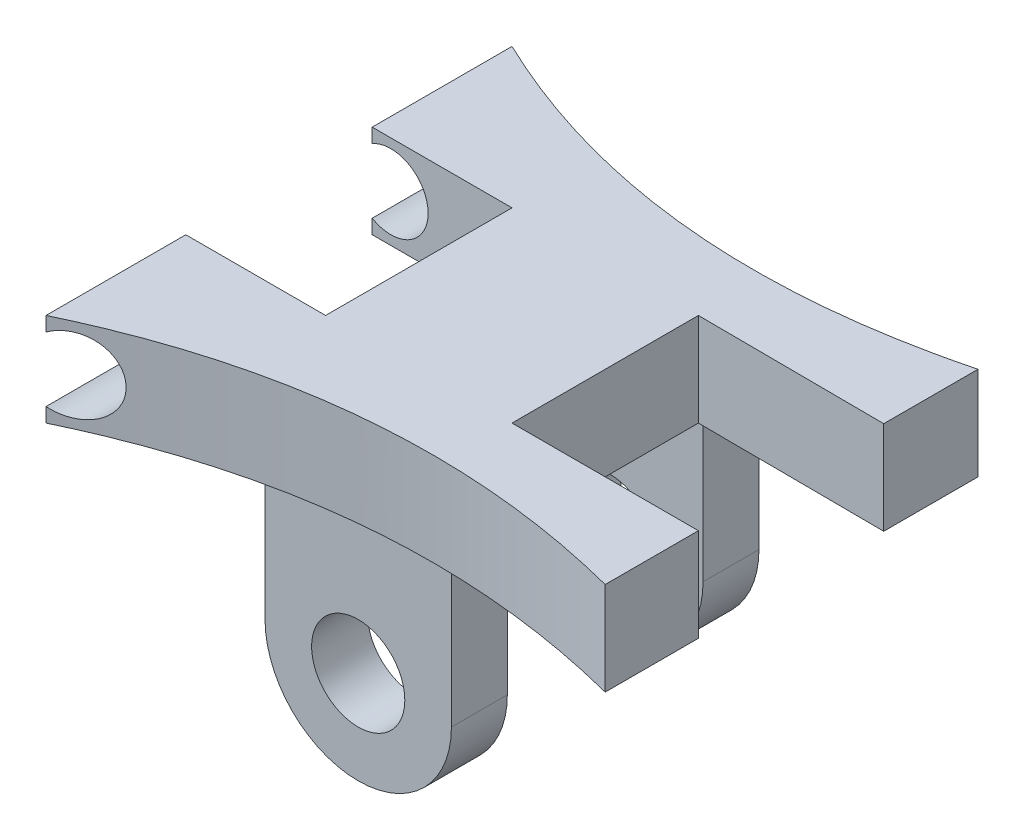
SolidWorks part; units mm, degrees
ref_plane "前视基准面" through (0, 0, 0) normal (0, 0, 1) x (1, 0, 0)
ref_plane "上视基准面" through (0, 0, 0) normal (0, 1, 0) x (1, 0, 0)
ref_plane "右视基准面" through (0, 0, 0) normal (1, 0, 0) x (0, 0, -1)
sketch "草图1" plane through (-242.2875, 0, 0) normal (-1, 0, 0) x (0, 0, 1)
  line L0 (526.9141, -174.4706) -> (488.4141, -241.1546) construction
  line L1 (526.9141, -174.4706) -> (565.4141, -241.1546) construction
  line L2 (488.4141, -241.1546) -> (488.4141, -251.1546)
  line L3 (565.4141, -241.1546) -> (565.4141, -251.1546)
  line L4 (488.4141, -241.1546) -> (565.4141, -241.1546)
  line L5 (488.4141, -251.1546) -> (565.4141, -251.1546)
  circle A0 centre (526.9141, -174.4706) radius 77 construction
extrude "凸台-拉伸1" add sketch "草图1" along normal blind 55
sketch "草图2" plane through (0, -241.1546, 0) normal (0, 1, 0) x (1, 0, 0)
  line L1 (-242.2875, -565.4141) -> (-242.2875, -488.4141) construction
  line L3 (-242.2875, -526.9141) -> (-297.2875, -526.9141) construction
  line L4 (-297.2875, -565.4141) -> (-297.2875, -488.4141) construction
  line L7 (-242.2875, -506.9141) -> (-242.2875, -488.4141)
  line L8 (-242.2875, -488.4141) -> (-297.2875, -488.4141)
  line L9 (-297.2875, -488.4141) -> (-297.2875, -501.9141)
  line L10 (-242.2875, -546.9141) -> (-242.2875, -565.4141)
  line L11 (-242.2875, -565.4141) -> (-297.2875, -565.4141)
  line L12 (-297.2875, -565.4141) -> (-297.2875, -551.9141)
  spline S0 degree 2 poles (-242.2875, -506.9141) (-271.2881, -514.3954) (-297.2875, -501.9141) knots 0 0 0 1 1 1
  spline S1 degree 2 poles (-242.2875, -546.9141) (-271.2881, -539.4329) (-297.2875, -551.9141) knots 0 0 0 1 1 1
extrude "切除-拉伸1" cut sketch "草图2" against normal through all
sketch "草图4" plane through (0, -251.1546, 0) normal (0, -1, 0) x (1, 0, 0)
  line L0 (-242.2875, 506.9141) -> (-242.2875, 546.9141) construction
  line L1 (-242.2875, 526.9141) -> (-242.2875, 536.9141)
  line L2 (-242.2875, 526.9141) -> (-242.2875, 517.0288)
  line L3 (-242.2875, 536.9141) -> (-262.2875, 536.9141)
  line L4 (-262.2875, 536.9141) -> (-262.2875, 516.9141)
  line L5 (-242.2875, 517.0288) -> (-262.2875, 516.9141)
  line L6 (-262.2875, 536.9141) -> (-282.2875, 536.9141)
  line L9 (-282.2875, 536.9141) -> (-282.2875, 516.9141)
  line L11 (-282.2875, 536.9141) -> (-297.2875, 536.9141)
  line L12 (-297.2875, 536.9141) -> (-297.2875, 516.9141)
  line L13 (-297.2875, 516.9141) -> (-282.2875, 516.9141)
extrude "切除-拉伸3" cut sketch "草图4" against normal blind 10
sketch "草图5" plane through (0, -251.1546, 0) normal (0, -1, 0) x (1, 0, 0)
  line L3 (-262.2875, 537.4141) -> (-282.2851, 537.4141)
  line L5 (-282.2851, 516.4141) -> (-262.2875, 516.4141)
  line L6 (-262.2875, 537.4141) -> (-262.2875, 543.4141)
  line L7 (-262.2875, 543.4141) -> (-282.2875, 543.4141)
  line L8 (-282.2875, 543.4141) -> (-282.2851, 537.4141)
  line L9 (-262.2875, 516.4141) -> (-262.2875, 510.4141)
  line L10 (-262.2875, 510.4141) -> (-282.2851, 510.4141)
  line L11 (-282.2851, 510.4141) -> (-282.2851, 516.4141)
extrude "凸台-拉伸2" add sketch "草图5" along normal blind 26
sketch "草图8" plane through (0, 0, 543.4141) normal (0, 0, 1) x (1, 0, 0)
  line L1 (-262.2875, -277.1546) -> (-282.2875, -277.1546) construction
  line L2 (-262.2875, -266.1546) -> (-262.2875, -277.1546)
  line L3 (-262.2875, -277.1546) -> (-282.2875, -277.1546)
  line L4 (-282.2875, -277.1546) -> (-282.2875, -266.1546)
  arc A0 (-282.2875, -266.1546) -> (-262.2875, -266.1546) centre (-272.2875, -266.1546) ccw
  circle A1 centre (-272.2875, -266.1546) radius 5
extrude "切除-拉伸4" cut sketch "草图8" against normal through all
sketch "草图9" plane through (-282.2875, 0, 0) normal (-1, 0, 0) x (0, 0, 1)
  line L0 (526.9141, -251.1546) -> (526.9141, -241.1546)
  line L1 (536.9141, -251.1546) -> (516.9141, -251.1546) construction
  line L2 (536.9141, -241.1546) -> (516.9141, -241.1546) construction
ref_plane "基准面1" through (0, 0, 526.9141) normal (0, 0, -1) x (-1, 0, 0)
sketch "草图10" plane through (0, 0, 526.9141) normal (0, 0, -1) x (-1, 0, 0)
  line L0 (282.2875, -251.1546) -> (282.2875, -246.1546)
  line L1 (282.2875, -246.1546) -> (295.2875, -246.1546) construction
  circle A0 centre (295.2875, -246.1546) radius 4
extrude "切除-拉伸5" cut sketch "草图10" against normal through all both and the other way through all
